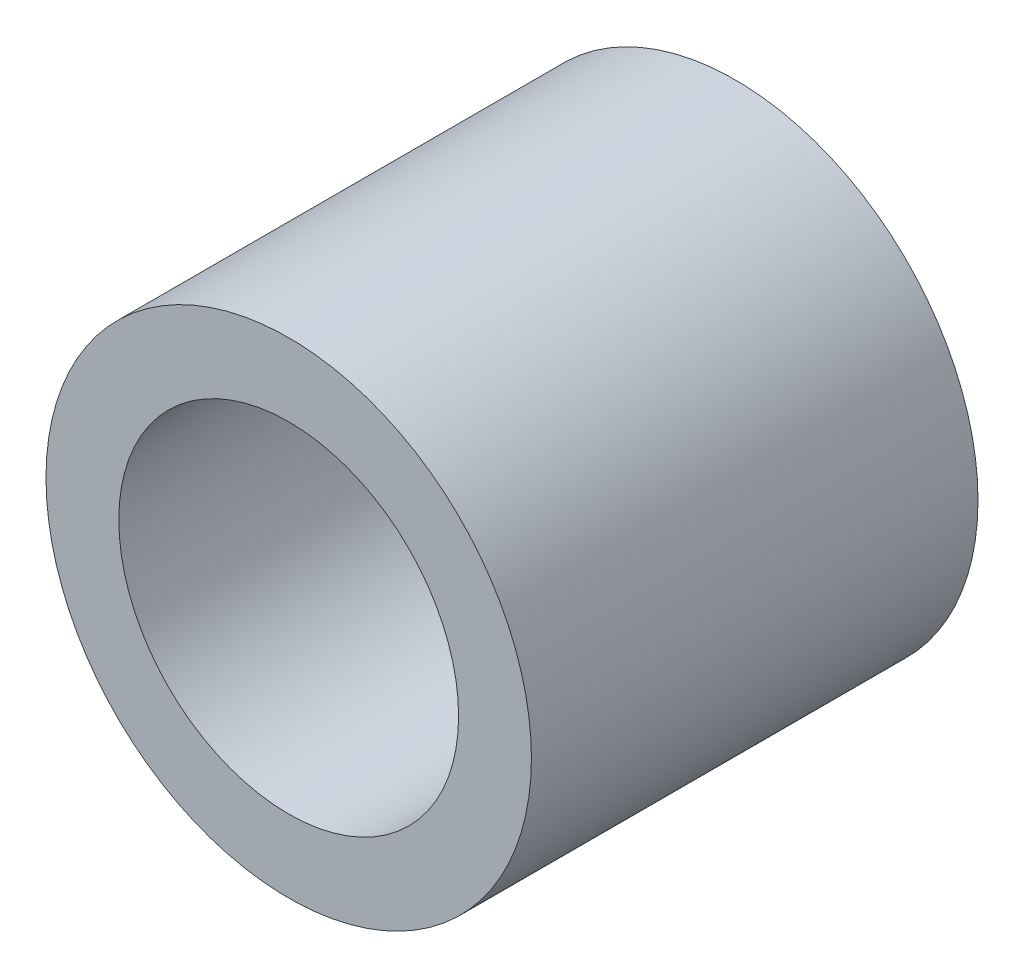
SolidWorks part; units mm, degrees
material "6061 合金"
ref_plane "前视基准面" through (0, 0, 0) normal (0, 0, 1) x (1, 0, 0)
ref_plane "上视基准面" through (0, 0, 0) normal (0, 1, 0) x (1, 0, 0)
ref_plane "右视基准面" through (0, 0, 0) normal (1, 0, 0) x (0, 0, -1)
sketch "草图1" plane through (0, 0, 0) normal (0, 0, 1) x (1, 0, 0)
  circle A0 centre (0, 0) radius 2.5
  circle A1 centre (0, 0) radius 1.75
  dimension "D1" = 5
  dimension "D2" = 3.5
extrude "凸台-拉伸1" add sketch "草图1" along normal blind 4.6
